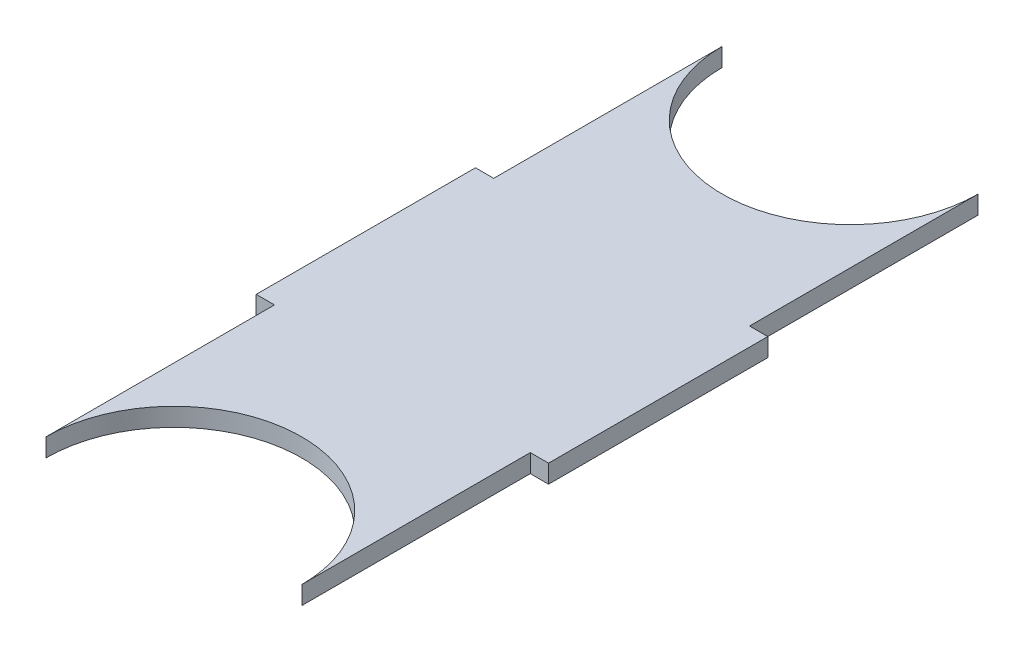
SolidWorks part; units mm, degrees
material "AISI 4130 Steel, annealed at 865C"
ref_plane "X-Y Datum" through (0, 0, 0) normal (0, 0, 1) x (1, 0, 0)
ref_plane "X-Z Datum" through (0, 0, 0) normal (0, 1, 0) x (1, 0, 0)
ref_plane "Y-Z Datum" through (0, 0, 0) normal (1, 0, 0) x (0, 0, -1)
sketch "Sketch1" plane through (0, 0, 0) normal (0, 1, 0) x (1, 0, 0)
  line L1 (11.1125, 27.7887) -> (-11.1125, 27.7887) construction
  line L2 (11.1125, 27.7887) -> (11.1125, -30.9637)
  line L3 (11.1125, -30.9637) -> (-11.1125, -30.9637) construction
  line L4 (-11.1125, 27.7887) -> (-11.1125, -30.9637)
  line L7 (11.1125, -11.1125) -> (12.7, -11.1125)
  line L8 (11.1125, -11.1125) -> (11.1125, 7.9375)
  line L9 (11.1125, 7.9375) -> (12.7, 7.9375)
  line L10 (12.7, -11.1125) -> (12.7, 7.9375)
  line L11 (-11.1125, -11.1125) -> (-12.7, -11.1125)
  line L12 (-11.1125, -11.1125) -> (-11.1125, 7.9375)
  line L13 (-11.1125, 7.9375) -> (-12.7, 7.9375)
  line L14 (-12.7, -11.1125) -> (-12.7, 7.9375)
  arc A0 (11.1125, -30.9637) -> (-11.1125, -30.9637) centre (0, -30.9637) ccw
  arc A1 (11.1125, 27.7887) -> (-11.1125, 27.7887) centre (0, 27.7887) cw
  point P0 (0, 0)
  point P2 (0, 0)
  point P4 (0, 0)
  point P16 (0, 0)
  point P17 (0, 0)
  dimension "D1" = 1.5875
  dimension "D2" = 25.4
  dimension "D3" = 19.05
  dimension "D4" = 11.1125
extrude "Boss-Extrude1" add sketch "Sketch1" along normal blind 1.5875
